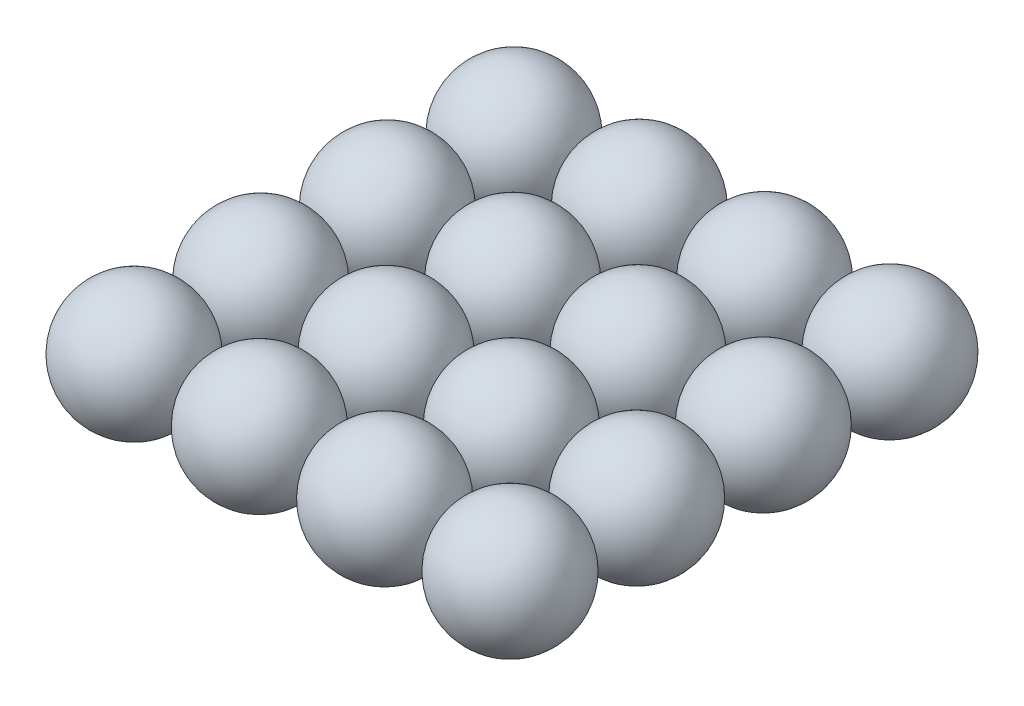
SolidWorks part; units mm, degrees
ref_plane "Front Plane" through (0, 0, 0) normal (0, 0, 1) x (1, 0, 0)
ref_plane "Top Plane" through (0, 0, 0) normal (0, 1, 0) x (1, 0, 0)
ref_plane "Right Plane" through (0, 0, 0) normal (1, 0, 0) x (0, 0, -1)
sketch "Sketch1" plane through (0, 0, 0) normal (0, 0, 1) x (1, 0, 0)
  line L0 (0, 95) -> (0, -95)
  arc A0 (0, 95) -> (0, -95) centre (0, 0) ccw
  dimension "D2" = 95
  dimension "D1" = 190
revolve "Revolve1" add sketch "Sketch1" angle 360 about L0
sketch "Sketch2" plane through (0, 0, 0) normal (0, 1, 0) x (1, 0, 0)
  line L0 (0, 0) -> (0, 573) construction
  line L1 (0, 0) -> (573, 0) construction
  point P3 (0, 0)
  dimension "D1" = 573
  dimension "D2" = 573
pattern_linear "LPattern6" count 4 spacing 193 along (0, 0, -1) of "Revolve1"
pattern_linear "LPattern7" count 4 spacing 191 along (1, 0, 0) of bodies 105 104 103 101
